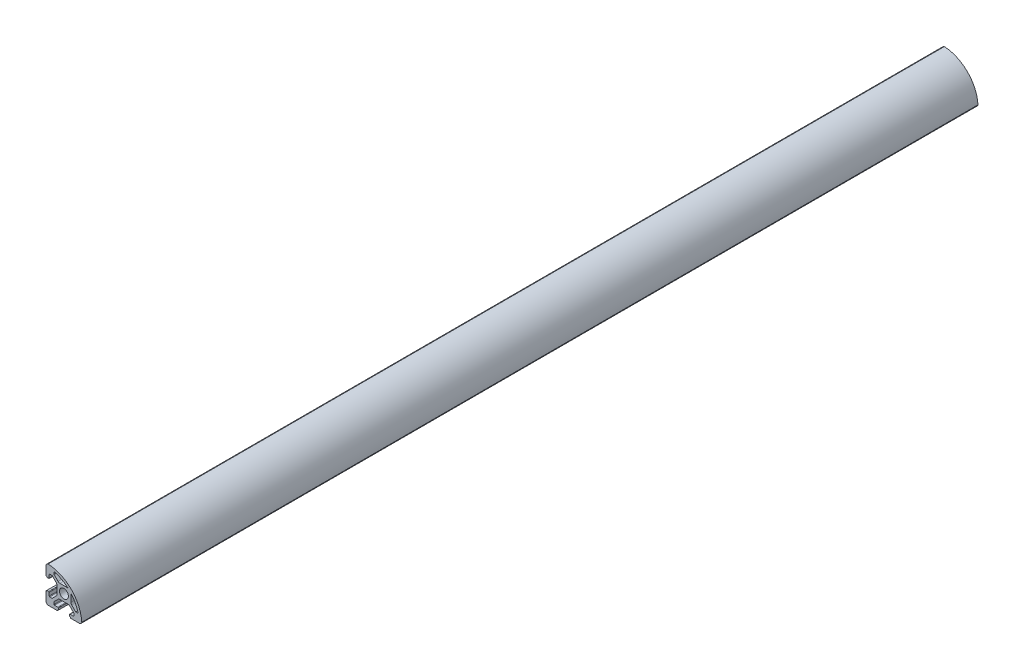
SolidWorks part; units mm, degrees
ref_plane "前视基准面" through (0, 0, 0) normal (0, 0, 1) x (1, 0, 0)
ref_plane "上视基准面" through (0, 0, 0) normal (0, 1, 0) x (1, 0, 0)
ref_plane "右视基准面" through (0, 0, 0) normal (1, 0, 0) x (0, 0, -1)
sketch "草图1" plane through (0, 0, 0) normal (0, 0, 1) x (1, 0, 0)
  line L14 (2.0848, 3.8649) -> (-2.342, 3.8649)
  line L15 (-3.4027, 4.3042) -> (-5.6233, 6.5249)
  line L16 (-5.6233, 6.5249) -> (-5.6233, 7.8649)
  line L22 (-10.1233, 8.4649) -> (-10.1233, 3.5649)
  line L23 (-10.1233, 3.5649) -> (-9.8233, 3.5649)
  line L24 (-9.6233, 3.3649) -> (-9.6233, 3.0649)
  line L25 (-9.6233, 3.0649) -> (-8.6233, 3.0649)
  line L26 (-8.3233, 3.3649) -> (-8.3233, 5.1649)
  line L27 (-8.0233, 5.4649) -> (-6.6833, 5.4649)
  line L28 (-6.6833, 5.4649) -> (-4.4627, 3.2442)
  line L29 (-4.0233, 2.1836) -> (-4.0233, -2.2538)
  line L30 (-4.4627, -3.3144) -> (-6.6833, -5.5351)
  line L31 (-6.6833, -5.5351) -> (-8.0233, -5.5351)
  line L32 (-8.3233, -5.2351) -> (-8.3233, -3.4351)
  line L33 (-8.6233, -3.1351) -> (-9.6233, -3.1351)
  line L34 (-9.6233, -3.1351) -> (-9.6233, -3.4351)
  line L35 (-9.8233, -3.6351) -> (-10.1233, -3.6351)
  line L36 (-10.1233, -3.6351) -> (-10.1233, -8.5351)
  line L37 (-8.6233, -10.0351) -> (-3.7233, -10.0351)
  line L38 (-3.7233, -10.0351) -> (-3.7233, -9.7351)
  line L39 (-3.5233, -9.5351) -> (-3.2233, -9.5351)
  line L40 (-3.2233, -9.5351) -> (-3.2233, -8.5351)
  line L41 (-3.5233, -8.2351) -> (-5.3233, -8.2351)
  line L42 (-5.6233, -7.9351) -> (-5.6233, -6.5951)
  line L43 (-5.6233, -6.5951) -> (-3.4027, -4.3744)
  line L44 (-2.342, -3.9351) -> (2.0953, -3.9351)
  line L45 (3.156, -4.3744) -> (5.3767, -6.5951)
  line L46 (5.3767, -6.5951) -> (5.3767, -7.9351)
  line L47 (5.0767, -8.2351) -> (3.2767, -8.2351)
  line L48 (2.9767, -8.5351) -> (2.9767, -9.5351)
  line L49 (2.9767, -9.5351) -> (3.2767, -9.5351)
  line L50 (3.4767, -9.7351) -> (3.4767, -10.0351)
  line L51 (3.4767, -10.0351) -> (8.3767, -10.0351)
  line L57 (7.7767, -5.5351) -> (6.4367, -5.5351)
  line L58 (6.4367, -5.5351) -> (4.216, -3.3144)
  line L59 (3.7767, -2.2538) -> (3.7767, 2.1836)
  circle A0 centre (-0.1233, -0.0351) radius 2.5
  arc A1 (7.8202, -5.5319) -> (3.7767, 2.1731) centre (-10.1233, -10.0351) ccw
  arc A2 (2.0848, 3.8649) -> (-5.6202, 7.9085) centre (-10.1233, -10.0351) ccw
  arc A9 (-3.4027, 4.3042) -> (-2.342, 3.8649) centre (-2.342, 5.3649) ccw
  arc A10 (-5.3233, 8.1649) -> (-5.6233, 7.8649) centre (-5.3233, 7.8649) ccw
  arc A13 (-8.6233, 9.9649) -> (-10.1233, 8.4649) centre (-8.6233, 8.4649) ccw
  arc A14 (-9.6233, 3.3649) -> (-9.8233, 3.5649) centre (-9.8233, 3.3649) ccw
  arc A15 (-8.6233, 3.0649) -> (-8.3233, 3.3649) centre (-8.6233, 3.3649) ccw
  arc A16 (-8.0233, 5.4649) -> (-8.3233, 5.1649) centre (-8.0233, 5.1649) ccw
  arc A17 (-4.0233, 2.1836) -> (-4.4627, 3.2442) centre (-5.5233, 2.1836) ccw
  arc A18 (-4.4627, -3.3144) -> (-4.0233, -2.2538) centre (-5.5233, -2.2538) ccw
  arc A19 (-8.3233, -5.2351) -> (-8.0233, -5.5351) centre (-8.0233, -5.2351) ccw
  arc A20 (-8.3233, -3.4351) -> (-8.6233, -3.1351) centre (-8.6233, -3.4351) ccw
  arc A21 (-9.8233, -3.6351) -> (-9.6233, -3.4351) centre (-9.8233, -3.4351) ccw
  arc A22 (-10.1233, -8.5351) -> (-8.6233, -10.0351) centre (-8.6233, -8.5351) ccw
  arc A23 (-3.5233, -9.5351) -> (-3.7233, -9.7351) centre (-3.5233, -9.7351) ccw
  arc A24 (-3.2233, -8.5351) -> (-3.5233, -8.2351) centre (-3.5233, -8.5351) ccw
  arc A25 (-5.6233, -7.9351) -> (-5.3233, -8.2351) centre (-5.3233, -7.9351) ccw
  arc A26 (-2.342, -3.9351) -> (-3.4027, -4.3744) centre (-2.342, -5.4351) ccw
  arc A27 (3.156, -4.3744) -> (2.0953, -3.9351) centre (2.0953, -5.4351) ccw
  arc A28 (5.0767, -8.2351) -> (5.3767, -7.9351) centre (5.0767, -7.9351) ccw
  arc A29 (3.2767, -8.2351) -> (2.9767, -8.5351) centre (3.2767, -8.5351) ccw
  arc A30 (3.4767, -9.7351) -> (3.2767, -9.5351) centre (3.2767, -9.7351) ccw
  arc A31 (8.3767, -10.0351) -> (9.8767, -8.5351) centre (8.3767, -8.5351) ccw
  arc A34 (7.7767, -5.5351) -> (7.8202, -5.5319) centre (7.7767, -5.2351) ccw
  arc A35 (3.7767, -2.2538) -> (4.216, -3.3144) centre (5.2767, -2.2538) ccw
  arc A37 (9.8419, -8.8562) -> (-8.9445, 9.9301) centre (-10.1233, -10.0351) ccw
extrude "凸台-拉伸1" add sketch "草图1" along normal blind 500 contours A31 A37 A13 L22 L23 A14 L24 L25 A15 L26 A16 L27 L28 A17 L29 A18 L30 L31 A19 L32 A20 L33 L34 A21 L35 L36 A22 L37 L38 A23 L39 L40 A24 L41 A25 L42 L43 A26 L44 A27 L45 L46 A28 L47 A29 L48 L49 A30 L50 L51
